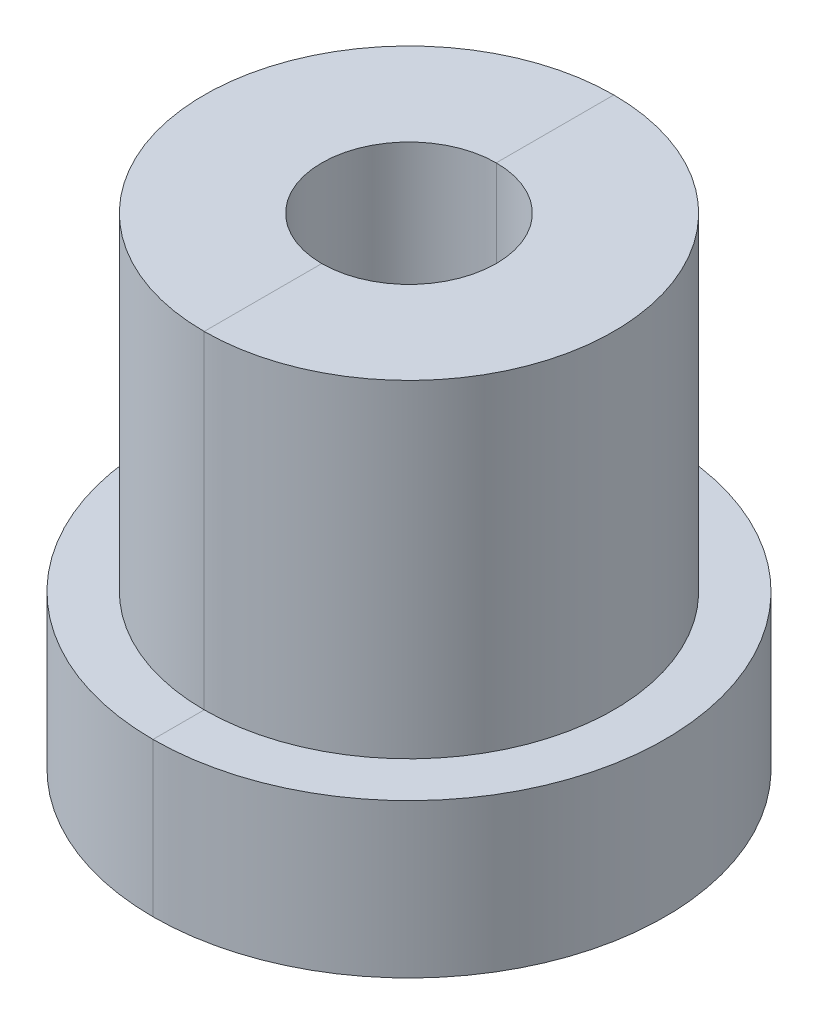
SolidWorks part; units mm, degrees
ref_plane "Front Plane" through (0, 0, 0) normal (0, 0, 1) x (1, 0, 0)
ref_plane "Top Plane" through (0, 0, 0) normal (0, 1, 0) x (1, 0, 0)
ref_plane "Right Plane" through (0, 0, 0) normal (1, 0, 0) x (0, 0, -1)
sketch "Sketch1" plane through (0, 0, 0) normal (0, 1, 0) x (1, 0, 0)
  circle A0 centre (0, 0) radius 7.9375
  dimension "D1" = 15.875
extrude "Boss-Extrude1" add sketch "Sketch1" along normal blind 4.7625
sketch "Sketch2" plane through (0, 4.7625, 0) normal (0, 1, 0) x (1, 0, 0)
  circle A0 centre (0, 0) radius 6.35
  dimension "D1" = 12.7
extrude "Boss-Extrude2" add sketch "Sketch2" along normal blind 10.16
sketch "Sketch3" plane through (0, 14.9225, 0) normal (0, 1, 0) x (1, 0, 0)
  circle A0 centre (0, 0) radius 2.7051
  dimension "D1" = 5.4102
extrude "Cut-Extrude1" cut sketch "Sketch3" against normal through all
split line "Split Line1"
